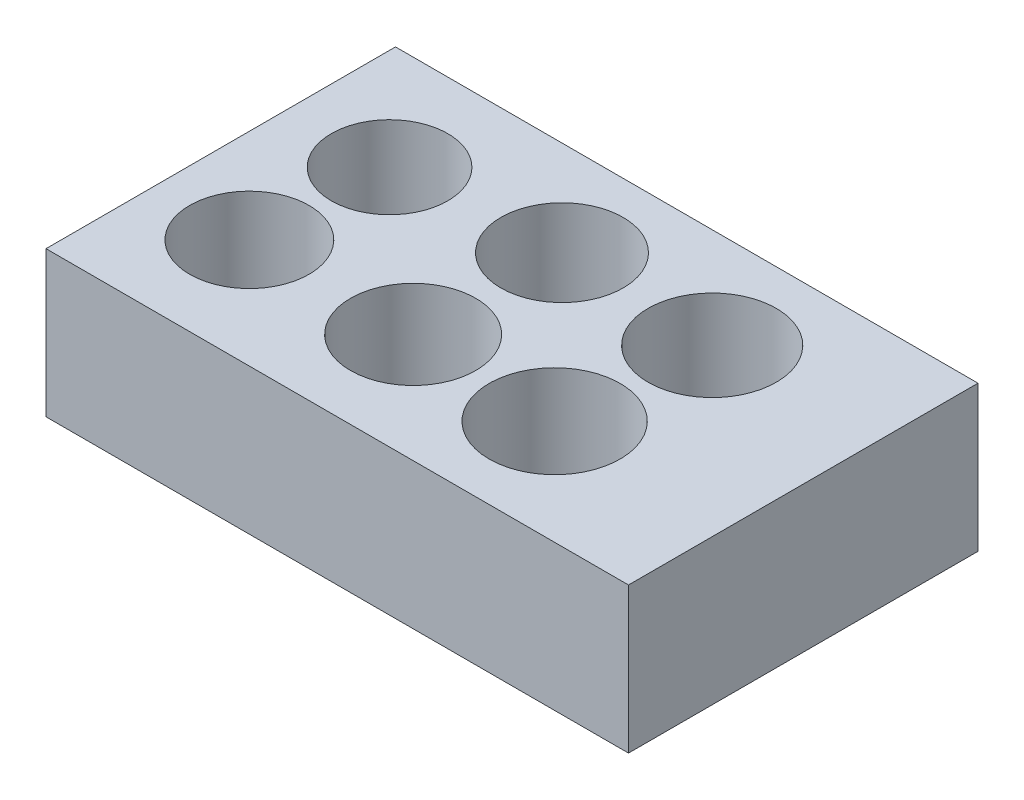
SolidWorks part; units mm, degrees
ref_plane "前视基准面" through (0, 0, 0) normal (0, 0, 1) x (1, 0, 0)
ref_plane "上视基准面" through (0, 0, 0) normal (0, 1, 0) x (1, 0, 0)
ref_plane "右视基准面" through (0, 0, 0) normal (1, 0, 0) x (0, 0, -1)
sketch "草图1" plane through (0, 0, 0) normal (0, 1, 0) x (1, 0, 0)
  line L1 (0, 0) -> (20, 0)
  line L2 (0, 0) -> (0, -12)
  line L3 (0, -12) -> (20, -12)
  line L4 (20, 0) -> (20, -12)
  dimension "D1" = 12
  dimension "D2" = 20
extrude "凸台-拉伸1" add sketch "草图1" along normal blind 5
sketch "草图2" plane through (0, 5, 0) normal (0, 1, 0) x (1, 0, 0)
  circle A0 centre (3.4763, -3.6802) radius 2
  circle A1 centre (3.2296, -8.247) radius 2.05
  circle A2 centre (8.9781, -3.2612) radius 2.1
  circle A3 centre (8.8526, -8.247) radius 2.15
  circle A4 centre (14.3104, -3.4371) radius 2.2
  circle A5 centre (13.8637, -8.3994) radius 2.25
  point P4 (0, 0)
  point P5 (3.2491, -7.1446)
  point P6 (0, 0)
  point P9 (8.8722, -2.5778)
  point P12 (8.8722, -7.1446)
  point P15 (13.8832, -2.5778)
  point P18 (13.8832, -7.1446)
  point P19 (0, 0)
  point P20 (0, 0)
  point P21 (0, 0)
  point P22 (0, 0)
  point P23 (0, 0)
  point P24 (0, 0)
  point P25 (13.6183, -7.4309)
  point P26 (13.8832, -7.2969)
  point P27 (0, 0)
  point P28 (0, 0)
  point P29 (14.0825, -2.3128)
  point P30 (0, 0)
  point P31 (0, 0)
  point P32 (0, 0)
  point P33 (0, 0)
  point P34 (8.9977, -2.1587)
  point P35 (14.0957, -1.9187)
  point P36 (0, 0)
  point P37 (0, 0)
  point P38 (0, 0)
  point P39 (14.3299, -2.3346)
  point P40 (0, 0)
extrude "切除-拉伸1" cut sketch "草图2" against normal blind 4
